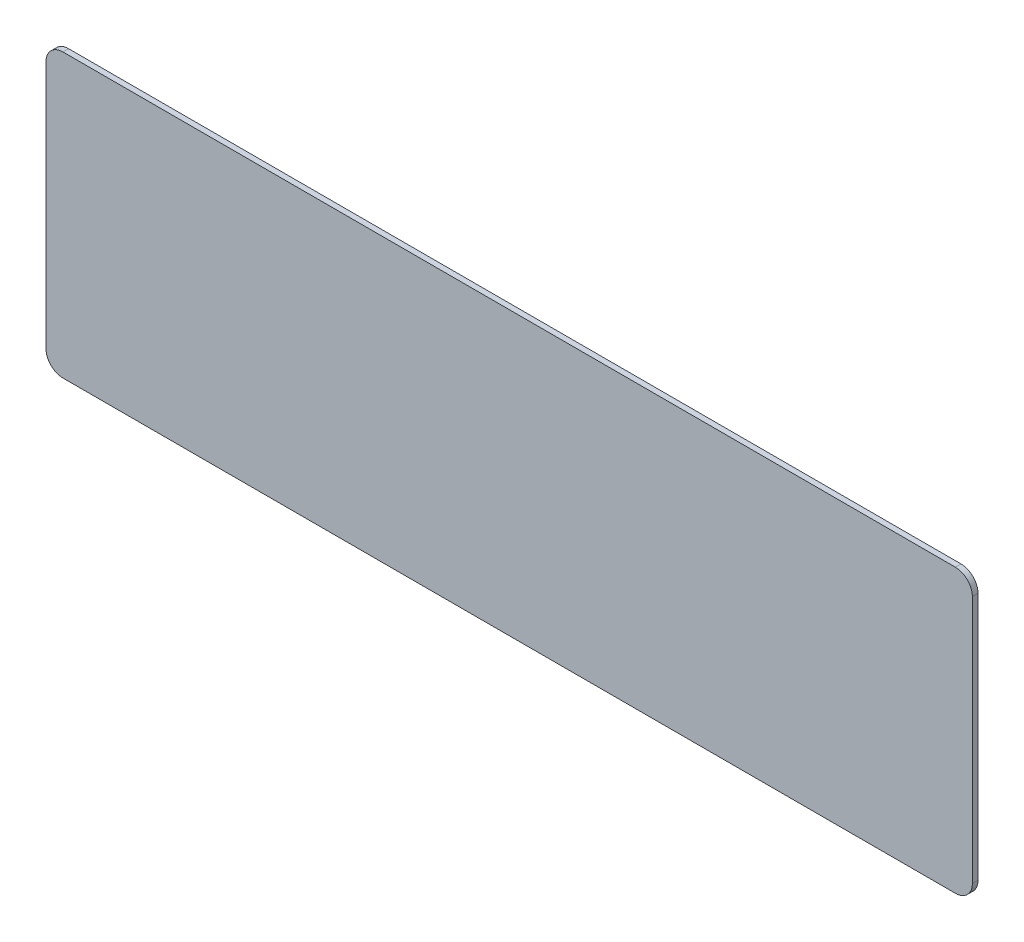
SolidWorks part; units mm, degrees
material "Thornel Mat VMA"
ref_plane "前视基准面" through (0, 0, 0) normal (0, 0, 1) x (1, 0, 0)
ref_plane "上视基准面" through (0, 0, 0) normal (0, 1, 0) x (1, 0, 0)
ref_plane "右视基准面" through (0, 0, 0) normal (1, 0, 0) x (0, 0, -1)
other "Configuration Table"
sketch "草图1" plane through (0, 0, 0) normal (0, 0, 1) x (1, 0, 0)
  line L1 (-82, 25) -> (82, 25)
  line L2 (-82, 25) -> (-82, -25)
  line L3 (-82, -25) -> (82, -25)
  line L4 (82, 25) -> (82, -25)
  line L5 (-82, 25) -> (82, -25) construction
  line L6 (-82, -25) -> (82, 25) construction
  point P0 (0, 0)
  dimension "D1" = 50
  dimension "D2" = 164
extrude "凸台-拉伸1" add sketch "草图1" along normal blind 1
fillet "圆角1" radius 3 4 edges at (82, -25, 0.5) (82, 25, 0.5) (-82, -25, 0.5) (-82, 25, 0.5)
